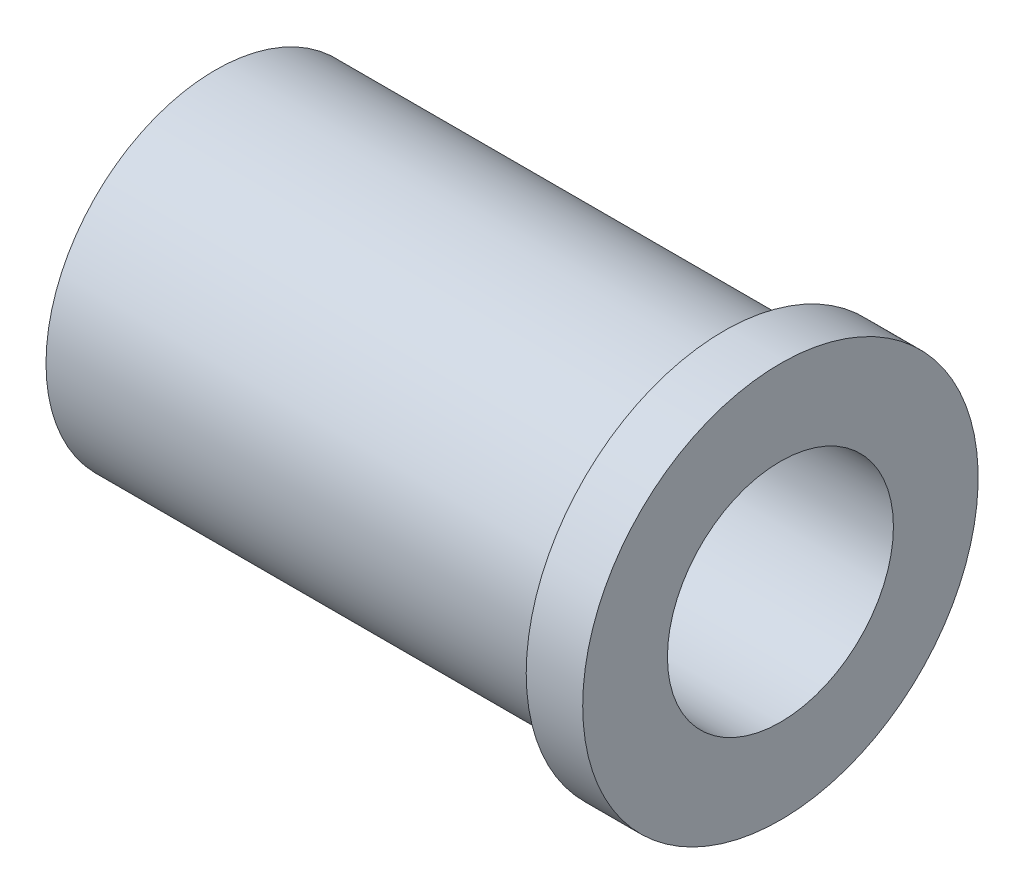
SolidWorks part; units mm, degrees
material "AISI 1015 Steel, Cold Drawn (SS)"
ref_plane "Front Plane" through (0, 0, 0) normal (0, 0, 1) x (1, 0, 0)
ref_plane "Top Plane" through (0, 0, 0) normal (0, 1, 0) x (1, 0, 0)
ref_plane "Right Plane" through (0, 0, 0) normal (1, 0, 0) x (0, 0, -1)
sketch "Sketch1" plane through (0, 0, 0) normal (0, 0, 1) x (1, 0, 0)
  line L0 (0, 0) -> (95.464, 0)
  line L2 (0, 20) -> (100, 20)
  line L3 (0, 20) -> (0, 30)
  line L4 (0, 30) -> (90, 30)
  line L5 (100, 20) -> (100, 30)
  line L7 (100, 30) -> (100, 35)
  line L8 (100, 35) -> (90, 35)
  line L9 (90, 30) -> (90, 35)
  dimension "D1" = 20
  dimension "D2" = 10
  dimension "D3" = 5
  dimension "D4" = 100
revolve "Revolve1" add sketch "Sketch1" angle 360 about L0
fillet "Fillet1" radius 4 1 edges at (0, 0, 20)
